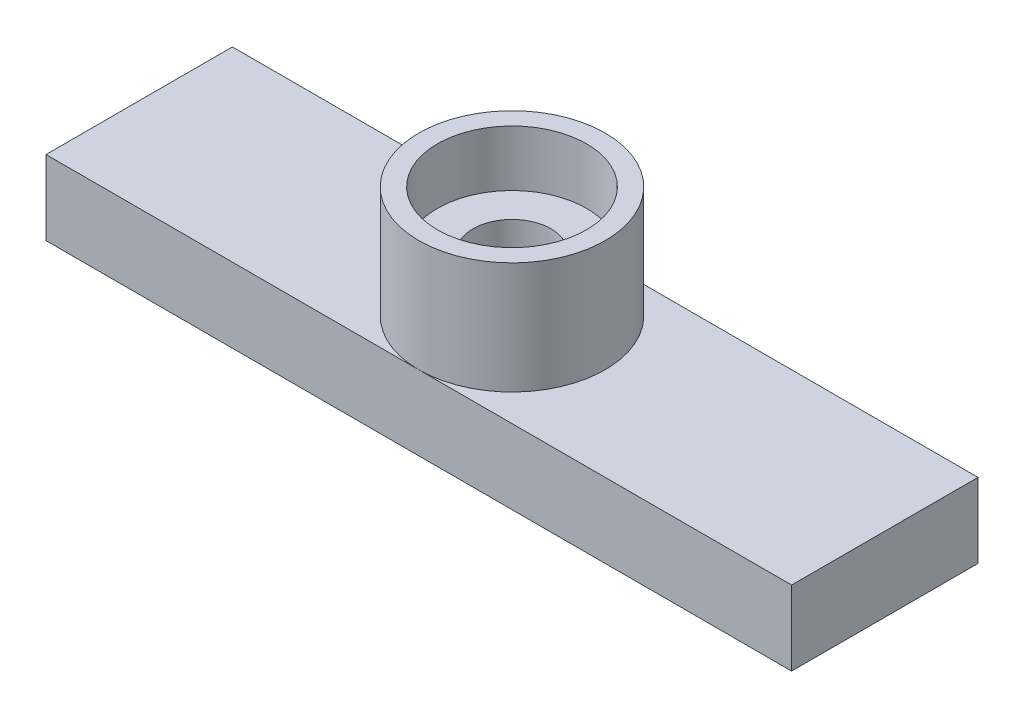
SolidWorks part; units mm, degrees
ref_plane "Front Plane" through (0, 0, 0) normal (0, 0, 1) x (1, 0, 0)
ref_plane "Top Plane" through (0, 0, 0) normal (0, 1, 0) x (1, 0, 0)
ref_plane "Right Plane" through (0, 0, 0) normal (1, 0, 0) x (0, 0, -1)
sketch "Sketch1" plane through (0, 0, 0) normal (0, 1, 0) x (1, 0, 0)
  circle A0 centre (0, 0) radius 2.1
  circle A1 centre (0, 0) radius 4
  dimension "D1" = 4.2
  dimension "D2" = 8
extrude "Boss-Extrude1" add sketch "Sketch1" along normal blind 3
sketch "Sketch2" plane through (0, 0, 0) normal (0, 1, 0) x (1, 0, 0)
  circle A0 centre (0, 0) radius 4
  circle A1 centre (0, 0) radius 5
  dimension "D1" = 8
  dimension "D2" = 10
extrude "Boss-Extrude2" add sketch "Sketch2" along normal blind 6
sketch "Sketch3" plane through (0, 0, 0) normal (0, 1, 0) x (1, 0, 0)
  line L1 (-20, -5) -> (20, -5)
  line L2 (-20, -5) -> (-20, 5)
  line L3 (-20, 5) -> (20, 5)
  line L4 (20, -5) -> (20, 5)
  line L5 (-20, -5) -> (20, 5) construction
  line L6 (-20, 5) -> (20, -5) construction
  circle A0 centre (0, 0) radius 4
  point P0 (0, 0)
  dimension "D1" = 8
  dimension "D2" = 10
  dimension "D3" = 40
extrude "Boss-Extrude3" add sketch "Sketch3" against normal blind 4
